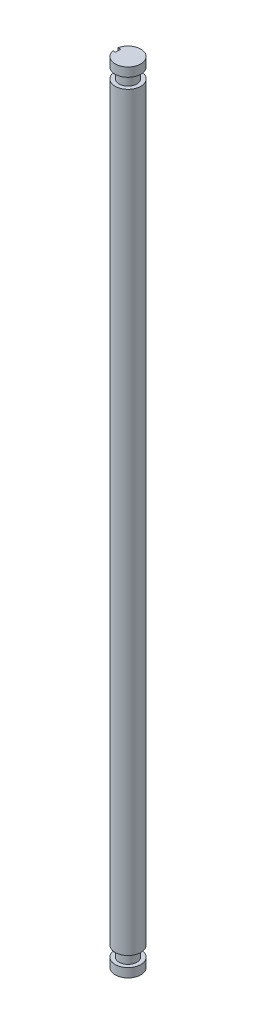
SolidWorks part; units mm, degrees
ref_plane "Front Plane" through (0, 0, 0) normal (1, 0, 0) x (0, 1, 0)
ref_plane "Top Plane" through (0, 0, 0) normal (0, 0, 1) x (0, 1, 0)
ref_plane "Right Plane" through (0, 0, 0) normal (0, 1, 0) x (-1, 0, 0)
sketch "Sketch1" plane through (0, 0, 0) normal (0, 0, 1) x (0, 1, 0)
  line L0 (-976.376, 0) -> (-976.376, 31.7309)
  line L1 (-976.376, 31.7309) -> (-954.024, 31.7309)
  line L2 (-954.024, 31.7309) -> (-954.024, 22.0218)
  line L3 (-954.024, 22.0218) -> (-928.2176, 22.0218)
  line L4 (-928.2176, 22.0218) -> (-928.2176, 31.7309)
  line L5 (-928.2176, 31.7309) -> (928.3446, 31.7309)
  line L6 (928.3446, 31.7309) -> (928.3446, 22.0218)
  line L7 (928.3446, 22.0218) -> (954.151, 22.0218)
  line L8 (954.151, 22.0218) -> (954.151, 31.7309)
  line L9 (954.151, 31.7309) -> (976.376, 31.7309)
  line L10 (976.376, 31.7309) -> (976.376, 0)
  line L11 (976.376, 0) -> (-976.376, 0)
  line L12 (-1001.776, 0) -> (1001.776, 0) construction
  point P14 (0, 0)
  dimension "D1" = 22.225
  dimension "D2" = 48.0314
  dimension "D3" = 1904.5936
  dimension "D4" = 1930.4
  dimension "D5" = 1952.752
  dimension "D6" = 9.7092
  dimension "D7" = 31.7309
revolve "Revolve1" add sketch "Sketch1" angle 360 about L12
sketch "Sketch2" plane through (0, 0, 0) normal (0, 1, 0) x (-1, 0, 0)
  line L1 (24.6062, -6.35) -> (88.0682, -6.35)
  line L2 (24.6062, -6.35) -> (24.6062, 6.35)
  line L3 (24.6062, 6.35) -> (88.0682, 6.35)
  line L4 (88.0682, -6.35) -> (88.0682, 6.35)
  point P8 (0, 0)
  dimension "D1" = 63.4619
  dimension "D2" = 12.7
  dimension "D3" = 88.0682
  dimension "D4" = 6.35
extrude "Cut-Extrude2" cut sketch "Sketch2" along normal blind 1997.456 from offset 998.728
